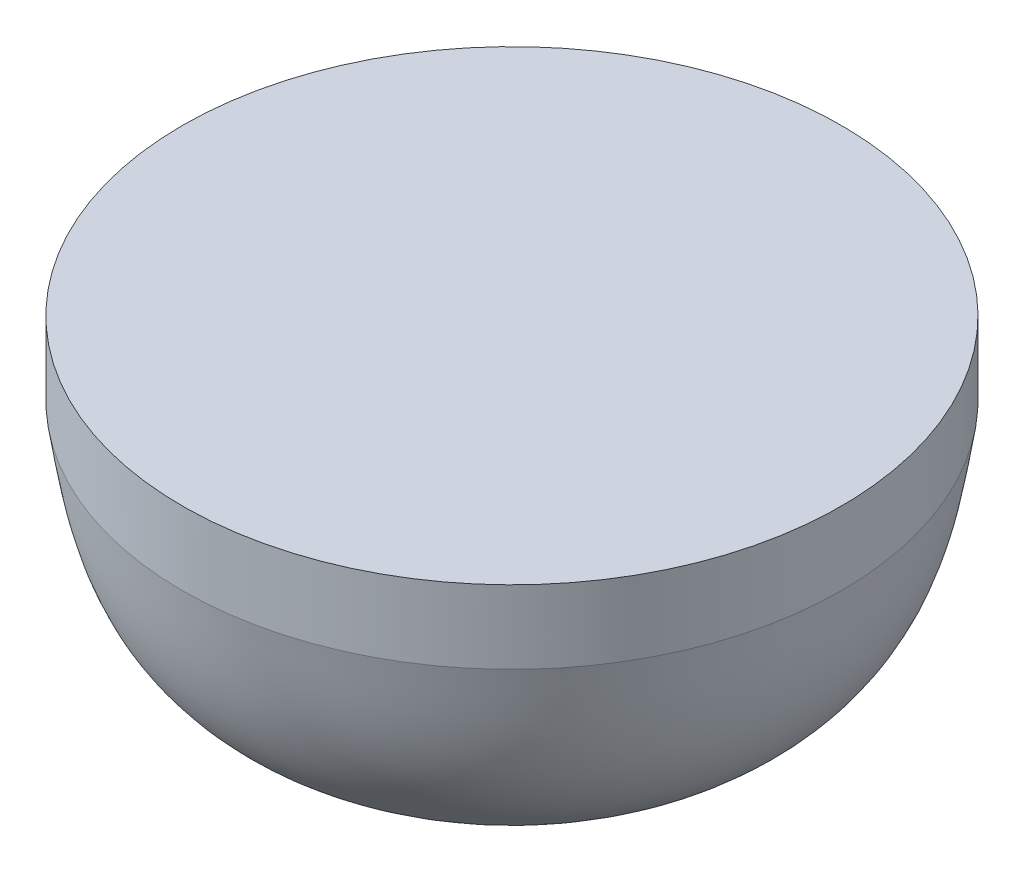
SolidWorks part; units mm, degrees
ref_plane "Front" through (0, 0, 0) normal (0, 0, 1) x (1, 0, 0)
ref_plane "Top" through (0, 0, 0) normal (0, 1, 0) x (1, 0, 0)
ref_plane "Right" through (0, 0, 0) normal (1, 0, 0) x (0, 0, -1)
sketch "Sketch1" plane through (0, 0, 0) normal (0, 0, 1) x (1, 0, 0)
  line L0 (0, 0) -> (0, -14)
  line L1 (-15, 0) -> (15, 0) construction
  line L2 (-15, 0) -> (-15, -9) construction
  line L3 (-15, -9) -> (15, -9) construction
  line L4 (15, 0) -> (15, -9) construction
  line L5 (0, 0) -> (18, 0) construction
  line L6 (18, 0) -> (15.6756, -14.676) construction
  line L7 (-15, -20) -> (15, -20) construction
  line L8 (-15, -17) -> (15, -17) construction
  line L9 (-15, -14) -> (15, -14) construction
  line L10 (18, 0) -> (18, 4)
  line L11 (18, 4) -> (0, 4)
  line L12 (0, 4) -> (0, 0)
  spline S0 degree 3 poles (0, -14) (16.3895, -14) (17.0195, -6.0548) (18, 0) knots 0 0 0 0 1 1 1 1
  dimension "D1" = 30
  dimension "D2" = 9
  dimension "D3" = 18
  dimension "D4" = 20
  dimension "D5" = 3
  dimension "D6" = 3
  dimension "D7" = 81
  dimension "D8" = 18
revolve "Revolve1" add sketch "Sketch1" angle 360 about L0
